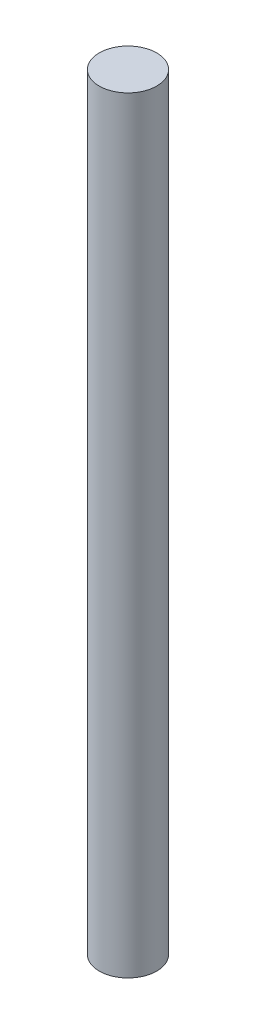
SolidWorks part; units mm, degrees
ref_plane "Front" through (0, 0, 0) normal (0, 0, 1) x (1, 0, 0)
ref_plane "Top" through (0, 0, 0) normal (0, 1, 0) x (1, 0, 0)
ref_plane "Right" through (0, 0, 0) normal (1, 0, 0) x (0, 0, -1)
sketch "Skizze1" plane through (0, 0, 0) normal (0, 1, 0) x (1, 0, 0)
  circle A0 centre (0, 0) radius 7.5
  dimension "D1" = 15
extrude "Aufsatz-Linear austragen1" add sketch "Skizze1" along normal blind 200
